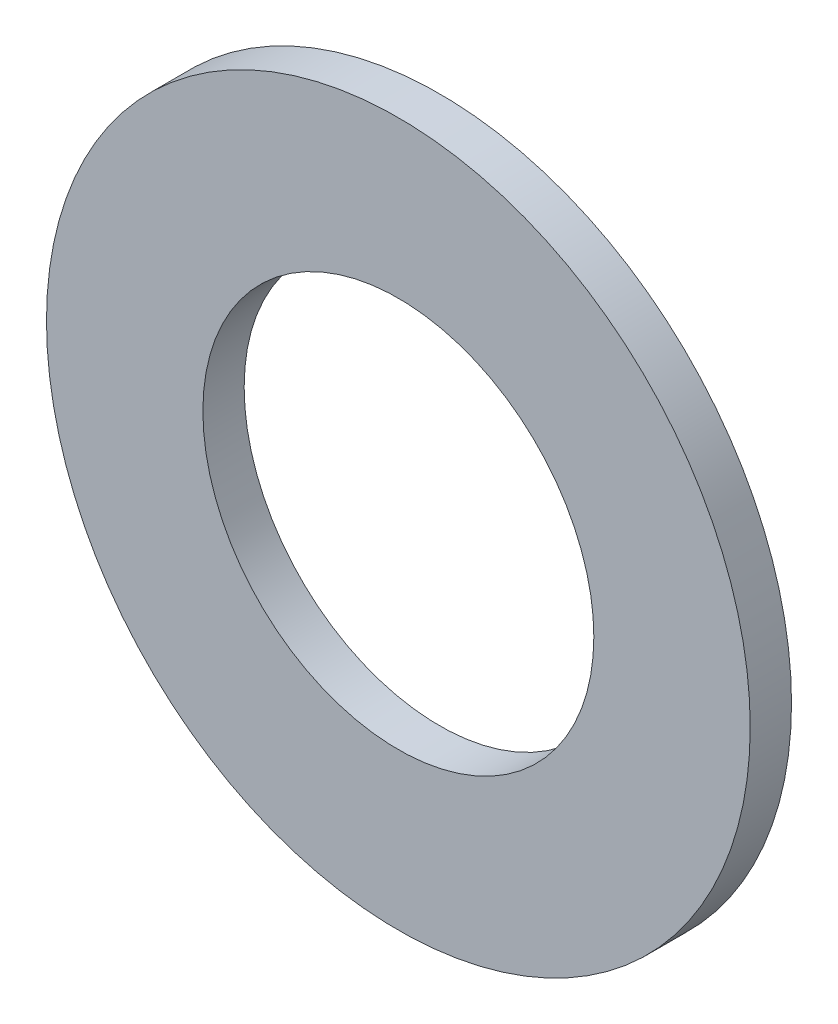
SolidWorks part; units mm, degrees
ref_plane "Front Plane" through (0, 0, 0) normal (0, 0, 1) x (1, 0, 0)
ref_plane "Top Plane" through (0, 0, 0) normal (0, 1, 0) x (1, 0, 0)
ref_plane "Right Plane" through (0, 0, 0) normal (1, 0, 0) x (0, 0, -1)
sketch "Sketch1" plane through (0, 0, 0) normal (0, 0, 1) x (1, 0, 0)
  circle A0 centre (0, 0) radius 7.9375
  circle A1 centre (0, 0) radius 14.2875
  dimension "D1" = 15.875
  dimension "D2" = 28.575
extrude "Boss-Extrude1" add sketch "Sketch1" along normal blind 1.6764
